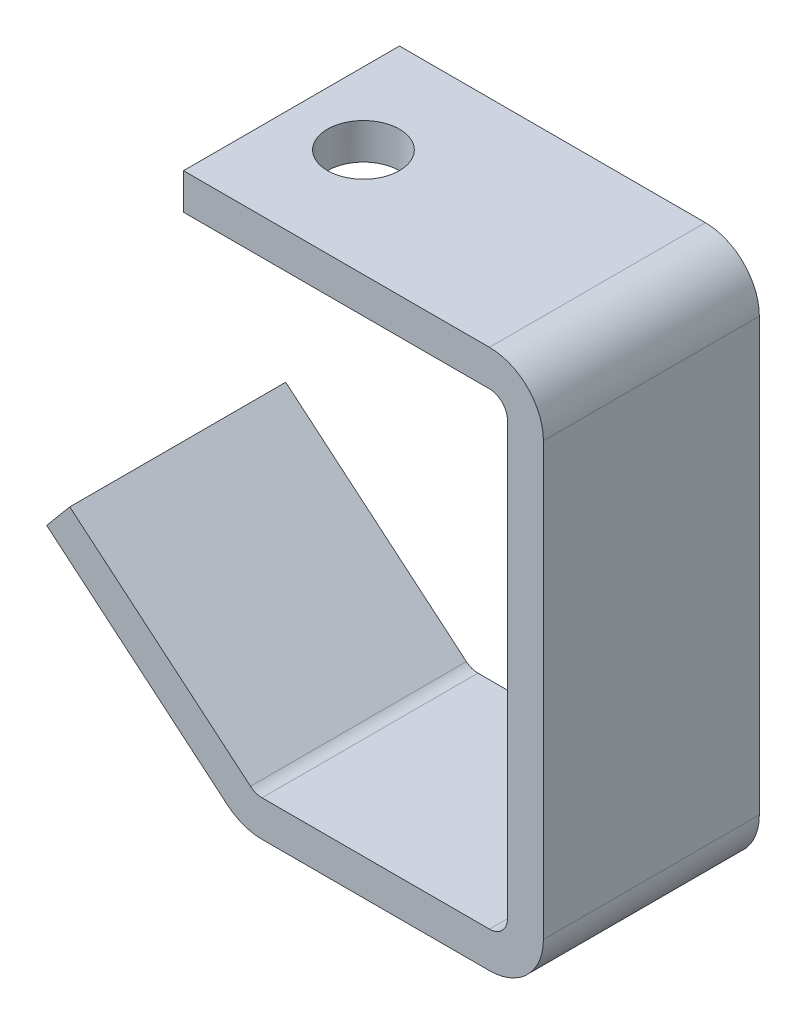
SolidWorks part; units mm, degrees
ref_plane "Front Plane" through (0, 0, 0) normal (0, 0, 1) x (1, 0, 0)
ref_plane "Top Plane" through (0, 0, 0) normal (0, 1, 0) x (1, 0, 0)
ref_plane "Right Plane" through (0, 0, 0) normal (1, 0, 0) x (0, 0, -1)
sketch "Sketch1" plane through (0, 0, 0) normal (0, 0, 1) x (1, 0, 0)
  line L0 (0, 0) -> (0, 82.55)
  line L1 (0, 82.55) -> (-57.15, 82.55)
  line L2 (-77.216, 27.494) -> (-44.45, 0)
  line L3 (-44.45, 0) -> (0, 0)
extrude "Extrude-Thin1" add sketch "Sketch1" along normal mid plane 38.1 thin
ref_plane "Plane1" through (0, 88.9, 0) normal (0, 1, 0) x (1, 0, 0)
sketch "Sketch2" plane through (0, 88.9, 0) normal (0, 1, 0) x (1, 0, 0)
  line L0 (0, 0) -> (-57.15, 0) construction
  circle A0 centre (-44.45, 0) radius 6.35
extrude "Cut-Extrude1" cut sketch "Sketch2" against normal blind 10
